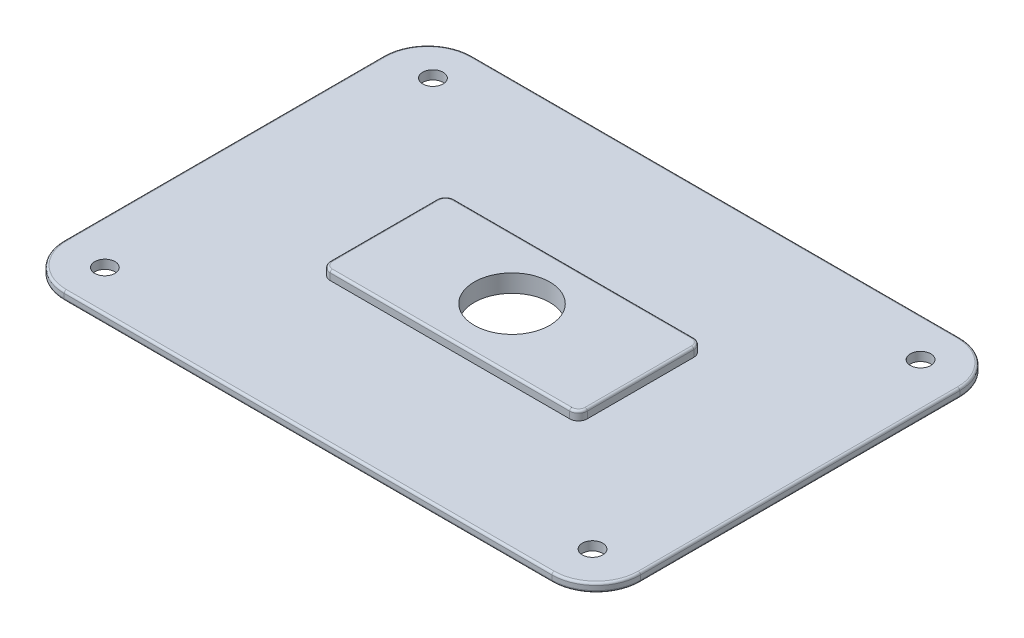
SolidWorks part; units mm, degrees
ref_plane "Front Plane" through (0, 0, 0) normal (0, 0, 1) x (1, 0, 0)
ref_plane "Top Plane" through (0, 0, 0) normal (0, 1, 0) x (1, 0, 0)
ref_plane "Right Plane" through (0, 0, 0) normal (1, 0, 0) x (0, 0, -1)
sketch "Sketch1" plane through (0, 0, 0) normal (0, 1, 0) x (1, 0, 0)
  line L5 (-10.0157, 82.8549) -> (119.9843, 82.8549)
  line L6 (-10.0157, 82.8549) -> (-10.0157, -9.1451)
  line L7 (-10.0157, -9.1451) -> (119.9843, -9.1451)
  line L8 (119.9843, 82.8549) -> (119.9843, -9.1451)
  circle A0 centre (0, 74) radius 2.3
  circle A1 centre (110, 74) radius 2.3
  circle A2 centre (110, 0) radius 2.3
  circle A3 centre (0, 0) radius 2.3
  dimension "D3" = 4.6
  dimension "D1" = 110
  dimension "D2" = 74
  dimension "D4" = 130
  dimension "D5" = 92
extrude "Boss-Extrude1" add sketch "Sketch1" along normal blind 2
sketch "Sketch2" plane through (0, 0, 0) normal (0, 1, 0) x (1, 0, 0)
  line L3 (25.9843, 22.8549) -> (83.9843, 22.8549)
  line L4 (25.9843, 22.8549) -> (25.9843, 50.8549)
  line L5 (83.9843, 22.8549) -> (83.9843, 50.8549)
  line L6 (25.9843, 50.8549) -> (83.9843, 50.8549)
  line L7 (25.9843, 22.8549) -> (83.9843, 50.8549) construction
  line L8 (83.9843, 22.8549) -> (25.9843, 50.8549) construction
  point P9 (54.9843, 36.8549)
  dimension "D1" = 58
  dimension "D2" = 28
extrude "Boss-Extrude2" add sketch "Sketch2" along normal blind 4
fillet "Fillet1" radius 10 4 edges at (119.9843, 1, -82.8549) (119.9843, 1, 9.1451) (-10.0157, 1, 9.1451) (-10.0157, 1, -82.8549)
fillet "Fillet2" radius 2 4 edges at (25.9843, 3, -50.8549) (83.9843, 3, -50.8549) (83.9843, 3, -22.8549) (25.9843, 3, -22.8549)
fillet "Fillet3" radius 0.5 24 edges at (-7.0868, 0, -79.926) (54.9843, 0, -82.8549) (117.0553, 0, -79.926) (119.9843, 0, -36.8549) (117.0553, 0, 6.2162) (54.9843, 0, 9.1451) (-7.0868, 0, 6.2162) (-7.0868, 2, -79.926) (54.9843, 2, -82.8549) (117.0553, 2, -79.926) (119.9843, 2, -36.8549) (117.0553, 2, 6.2162) (54.9843, 2, 9.1451) (-7.0868, 2, 6.2162) (83.3985, 4, -50.2691) (83.9843, 4, -36.8549) (83.3985, 4, -23.4407) (54.9843, 4, -22.8549) (26.57, 4, -23.4407) (25.9843, 4, -36.8549) (26.57, 4, -50.2691) (-10.0157, 0, -36.8549) (-10.0157, 2, -36.8549) (54.9843, 4, -50.8549)
sketch "Sketch3" plane through (0, 0, 0) normal (0, 1, 0) x (1, 0, 0)
  circle A4 centre (54.9843, 36.8549) radius 8.5
extrude "Cut-Extrude1" cut sketch "Sketch3" along normal through all
